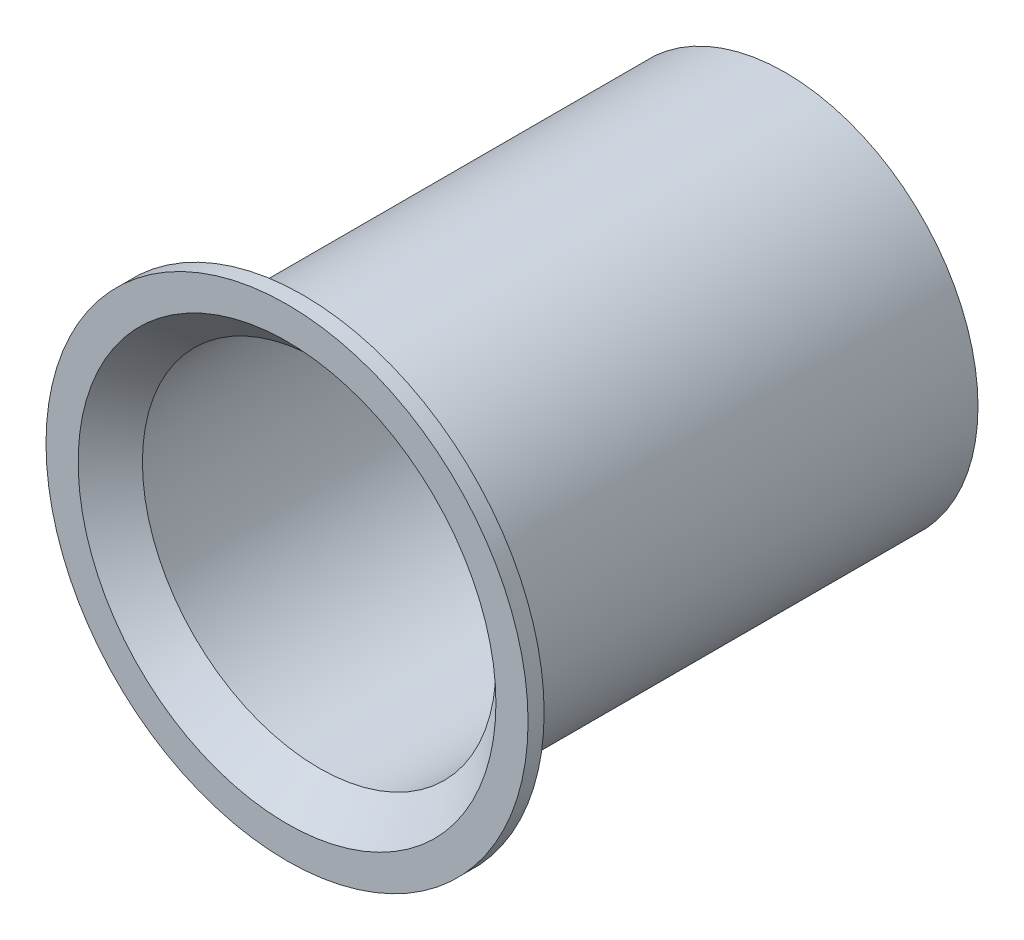
SolidWorks part; units mm, degrees
ref_plane "Front Plane" through (0, 0, 0) normal (0, 0, 1) x (1, 0, 0)
ref_plane "Top Plane" through (0, 0, 0) normal (0, 1, 0) x (1, 0, 0)
ref_plane "Right Plane" through (0, 0, 0) normal (1, 0, 0) x (0, 0, -1)
sketch "Sketch1" plane through (0, 0, 0) normal (0, 0, 1) x (1, 0, 0)
  circle A0 centre (0, 0) radius 7.5
extrude "Boss-Extrude1" add sketch "Sketch1" along normal blind 0.5
sketch "Sketch2" plane through (0, 0, 0) normal (0, 0, -1) x (-1, 0, 0)
  circle A0 centre (0, 0) radius 6
extrude "Boss-Extrude2" add sketch "Sketch2" along normal blind 15
sketch "Sketch3" plane through (0, 0, 0.5) normal (0, 0, 1) x (1, 0, 0)
  circle A0 centre (0, 0) radius 5.5
extrude "Cut-Extrude1" cut sketch "Sketch3" against normal through all
chamfer "Chamfer1" distance 1 angle 45 2 edges at (5.5, 0, 0.5) (-6, 0, 0)
